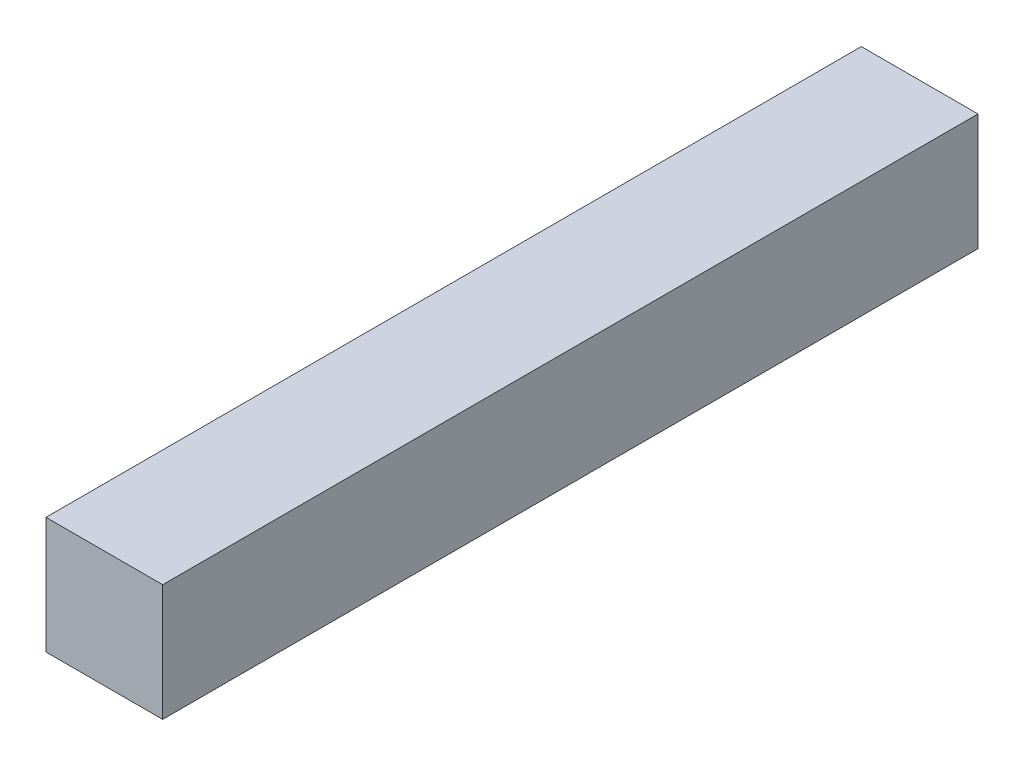
SolidWorks part; units mm, degrees
ref_plane "Front Plane" through (0, 0, 0) normal (0, 0, 1) x (1, 0, 0)
ref_plane "Top Plane" through (0, 0, 0) normal (0, 1, 0) x (1, 0, 0)
ref_plane "Right Plane" through (0, 0, 0) normal (1, 0, 0) x (0, 0, -1)
sketch "Sketch1" plane through (0, 0, 0) normal (0, 0, 1) x (1, 0, 0)
  line L0 (0.13, 0.13) -> (0.13, 15.87)
  line L1 (0, 0) -> (16, 0)
  line L2 (0, 0) -> (0, 16)
  line L4 (16, 0) -> (16, 16)
  line L5 (0.13, 15.87) -> (15.87, 15.87)
  line L6 (15.87, 0.13) -> (15.87, 15.87)
  line L7 (0.13, 0.13) -> (15.87, 0.13)
  line L8 (0, 16) -> (16, 16) construction
  dimension "D1" = 0.13
extrude "Boss-Extrude2" add sketch "Sketch1" along normal blind 110 contours L0 L7 L6 L5
